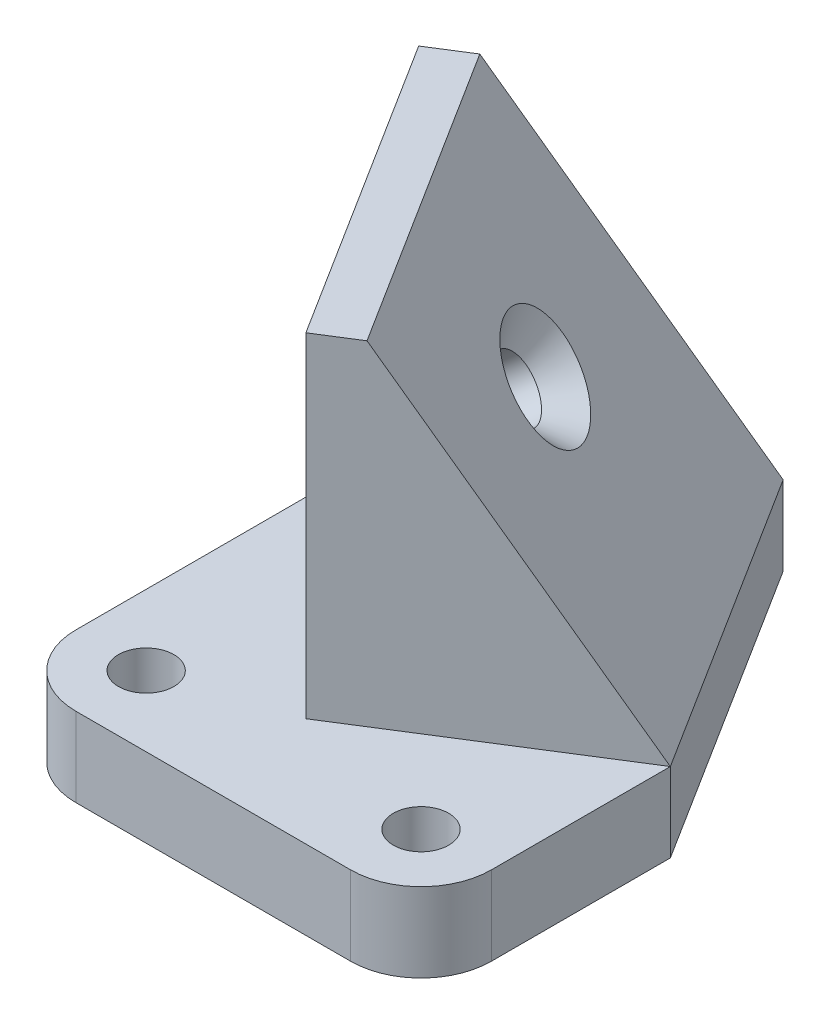
SolidWorks part; units mm, degrees
ref_plane "Front" through (0, 0, 0) normal (0, 0, 1) x (1, 0, 0)
ref_plane "Top" through (0, 0, 0) normal (0, 1, 0) x (1, 0, 0)
ref_plane "Right" through (0, 0, 0) normal (1, 0, 0) x (0, 0, -1)
sketch "Sketch1" plane through (0, 0, 0) normal (0, 1, 0) x (1, 0, 0)
  line L0 (0, 0) -> (0, 45)
  line L1 (0, 45) -> (-34.641, 100)
  line L2 (0, 0) -> (-75, 0)
  line L3 (-75, 0) -> (-75, 74.5804)
  line L4 (-34.641, 100) -> (-75, 74.5804)
  dimension "D1" = 75
  dimension "D2" = 45
  dimension "D3" = 32.204
  dimension "D4" = 65
  dimension "D5" = 100
extrude "Base-Extrude" add sketch "Sketch1" along normal blind 14.2875
sketch "Sketch2" plane through (0, 14.2875, 0) normal (0, 1, 0) x (-1, 0, 0)
  line L0 (34.641, -100) -> (75, -74.5804)
  line L1 (75, -74.5804) -> (40.359, -19.5804)
  line L2 (34.641, -100) -> (0, -45)
  line L3 (0, -45) -> (40.359, -19.5804)
extrude "Boss-Extrude1" add sketch "Sketch2" along normal blind 60.325
sketch "Sketch3" plane through (-20.2927, 0, -32.2189) normal (0.5329, 0, 0.8462) x (0.8462, 0, -0.5329)
  line L0 (-15.7147, 74.6125) -> (23.9822, 14.2875)
  line L1 (23.9822, 74.6125) -> (-23.7147, 74.6125) construction
  line L2 (-23.7147, 74.6125) -> (-23.7147, 14.2875) construction
  line L4 (23.9822, 74.6125) -> (23.9822, 14.2875) construction
  dimension "D1" = 8
  dimension "D2" = 33.347
extrude "Cut-Extrude1" cut sketch "Sketch3" against normal through all
hole_wizard "CSK for M10 Flat Head Machine Screw1" positions "Sketch6" profile "Sketch5" countersink size "M10" standard "Ansi Metric"
sketch "Sketch6" plane through (19.7121, 15.3301, -12.4154) normal (0.7068, 0.5497, -0.4452) x (-0.3678, -0.252, -0.8951)
  line L0 (98.6509, 29.9065) -> (76.8651, 98.7566) construction
  line L1 (14.8935, 79.1473) -> (76.8651, 98.7566) construction
  point P0 (53.6091, 60.4335)
  dimension "D1" = 33.7338
  dimension "D2" = 29.5216
sketch "Sketch5" plane through (-36.5211, 49.9514, -58.9486) normal (-0.104, 0.7033, 0.7033) x (-0.6997, 0.4508, -0.5543)
  line L0 (0, 0) -> (0, 28.7047)
  line L1 (0, 28.7047) -> (5.5, 25.4)
  line L2 (5.5, 25.4) -> (5.5, 4.5)
  line L3 (5.5, 4.5) -> (10, 0)
  line L5 (10, 0) -> (0, 0)
  line L6 (-5.5, 4.5) -> (-10, 0) construction
  line L10 (0, 28.7047) -> (-5.5, 25.4) construction
  line L11 (0, -6.35) -> (0, 107.95) construction
  dimension "Hole Dia." = 11
  dimension "Hole Depth" = 25.4
  dimension "Near C'Sink Dia." = 20
  dimension "Near C'Sink Angle" = 90
  dimension "Drill Angle" = 118
fillet "Fillet1" radius 12.7 2 edges at (0, 7.1437, 0) (-75, 7.1437, 0)
hole_wizard "Ø10.0 (10) Diameter Hole1" positions "Sketch9" profile "Sketch8" hole size "Ø10.0" standard "Ansi Metric" end condition through all
sketch "Sketch9" plane through (0, 14.2875, 0) normal (0, 1, 0) x (-1, 0, 0)
  line L0 (0, -12.7) -> (0, -45) construction
  arc A0 (75, -12.7) -> (62.3, 0) centre (62.3, -12.7) ccw construction
  point P0 (12.7, -12.7)
  point P1 (62.3, -12.7)
sketch "Sketch8" plane through (-12.7, 14.2875, -12.7) normal (1, 0, 0) x (0, 0, 1)
  line L0 (0, 0) -> (0, 14.2875)
  line L1 (0, 14.2875) -> (5, 14.2875)
  line L2 (5, 14.2875) -> (5, 0)
  line L5 (5, 0) -> (0, 0)
  line L11 (0, -6.35) -> (0, 28.9116) construction
  dimension "Thru Hole Dia." = 10
  dimension "Thru Hole Depth" = 14.2875
